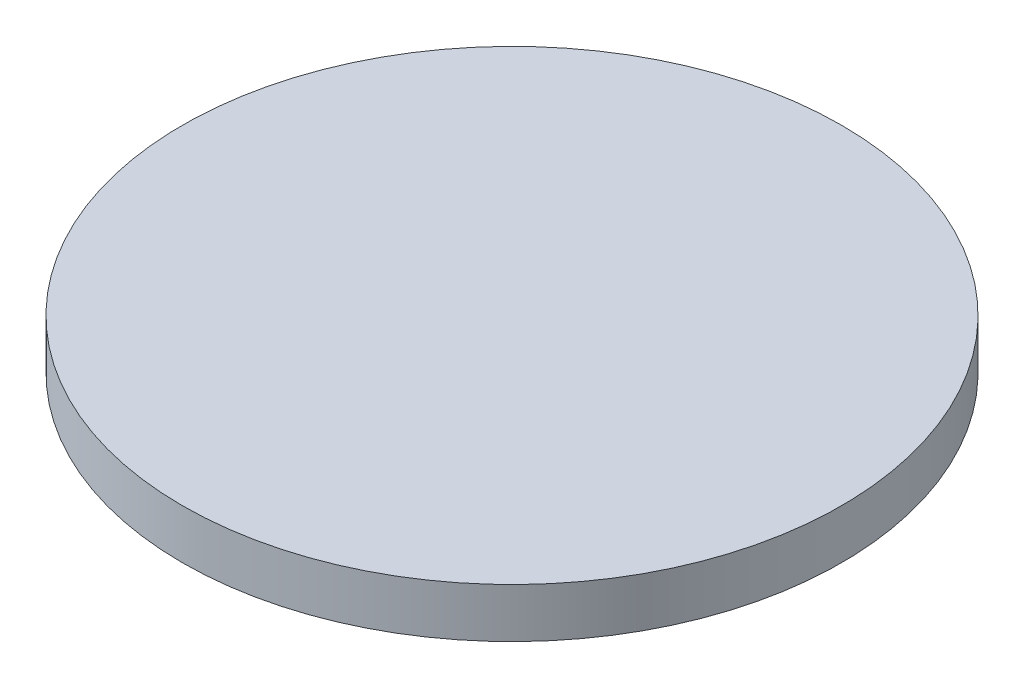
SolidWorks part; units mm, degrees
ref_plane "Спереди" through (0, 0, 0) normal (0, 0, 1) x (1, 0, 0)
ref_plane "Сверху" through (0, 0, 0) normal (0, 1, 0) x (1, 0, 0)
ref_plane "Справа" through (0, 0, 0) normal (1, 0, 0) x (0, 0, -1)
sketch "Эскиз1" plane through (0, 0, 0) normal (0, 1, 0) x (1, 0, 0)
  circle A0 centre (0, 0) radius 20
  dimension "D1" = 40
extrude "База" add sketch "Эскиз1" along normal blind 3
